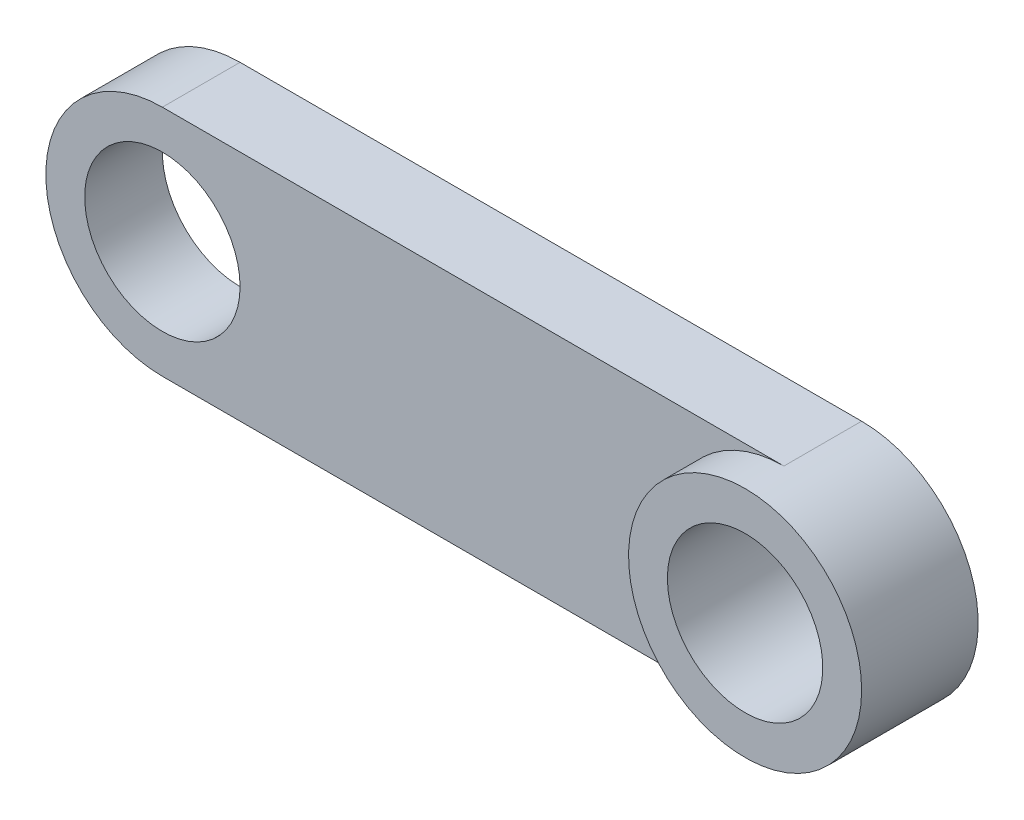
SolidWorks part; units mm, degrees
material "PVC Rigid"
ref_plane "Front Plane" through (0, 0, 0) normal (0, 0, 1) x (1, 0, 0)
ref_plane "Top Plane" through (0, 0, 0) normal (0, 1, 0) x (1, 0, 0)
ref_plane "Right Plane" through (0, 0, 0) normal (1, 0, 0) x (0, 0, -1)
sketch "Sketch1" plane through (0, 0, 0) normal (0, 0, 1) x (1, 0, 0)
  line L1 (-30.7464, 10.5651) -> (20.0536, 10.5651)
  line L3 (-30.7464, -8.4849) -> (20.0536, -8.4849)
  arc A0 (-30.7464, 10.5651) -> (-30.7464, -8.4849) centre (-30.7464, 1.0401) ccw
  arc A1 (20.0536, 10.5651) -> (20.0536, -8.4849) centre (20.0536, 1.0401) cw
  circle A2 centre (-30.7464, 1.0401) radius 6.35
  circle A3 centre (20.0536, 1.0401) radius 6.35
  point P8 (29.5786, 1.0401)
  point P9 (-40.2714, 1.0401)
  dimension "D1" = 69.85
  dimension "D2" = 19.05
extrude "Boss-Extrude1" add sketch "Sketch1" along normal blind 6.35
sketch "Sketch2" plane through (0, 0, 6.35) normal (0, 0, 1) x (1, 0, 0)
  circle A0 centre (20.0536, 1.0401) radius 9.525
extrude "Boss-Extrude2" add sketch "Sketch2" along normal blind 3.175
sketch "Sketch3" plane through (0, 0, 0) normal (0, 0, -1) x (-1, 0, 0)
  circle A0 centre (-20.0536, 1.0401) radius 6.35
extrude "Cut-Extrude1" cut sketch "Sketch3" against normal through all
